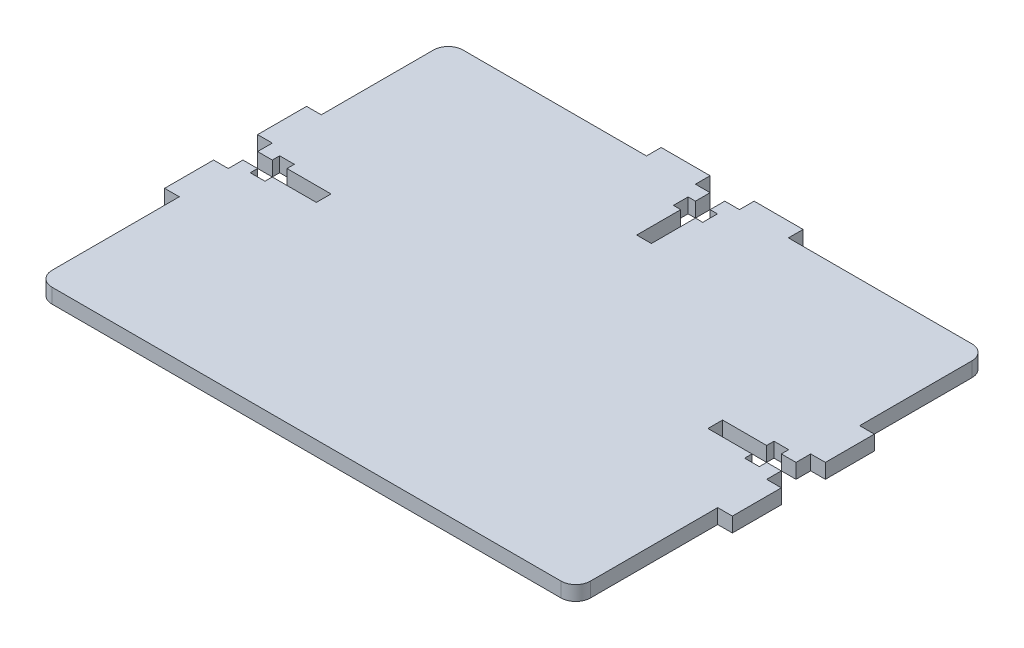
SolidWorks part; units mm, degrees
material "Acrylic (Medium-high impact)"
ref_plane "Front Plane" through (0, 0, 0) normal (0, 0, 1) x (1, 0, 0)
ref_plane "Top Plane" through (0, 0, 0) normal (0, 1, 0) x (1, 0, 0)
ref_plane "Right Plane" through (0, 0, 0) normal (1, 0, 0) x (0, 0, -1)
sketch "Sketch1" plane through (0, 0, 0) normal (0, 1, 0) x (1, 0, 0)
  line L0 (55, 83.95) -> (55, 0) construction
  line L1 (0, 0) -> (110, 0)
  line L2 (0, 83.95) -> (0, 0)
  line L3 (0, 83.95) -> (110, 83.95)
  line L4 (110, 83.95) -> (110, 0)
  line L5 (0, 41.975) -> (110, 41.975) construction
  line L6 (69.5, 83.95) -> (59.5, 83.95)
  line L7 (53.5, 83.95) -> (56.5, 83.95)
  line L8 (53.5, 83.95) -> (53.5, 68.95)
  line L9 (53.5, 68.95) -> (56.5, 68.95)
  line L10 (56.5, 83.95) -> (56.5, 68.95)
  line L11 (40.5, 83.95) -> (50.5, 83.95)
  line L12 (40.5, 83.95) -> (40.5, 86.95)
  line L13 (40.5, 86.95) -> (50.5, 86.95)
  line L14 (50.5, 83.95) -> (50.5, 86.95)
  line L15 (69.5, 83.95) -> (69.5, 86.95)
  line L16 (69.5, 86.95) -> (59.5, 86.95)
  line L17 (59.5, 83.95) -> (59.5, 86.95)
  line L19 (52, 80.95) -> (58, 80.95)
  line L20 (52, 80.95) -> (52, 77.95)
  line L21 (52, 77.95) -> (58, 77.95)
  line L22 (15, 43.5) -> (0, 43.5) construction
  line L23 (0, 45) -> (15, 45)
  line L24 (0, 45) -> (0, 42)
  line L25 (0, 42) -> (15, 42)
  line L26 (15, 45) -> (15, 42)
  line L27 (3, 46.5) -> (6, 46.5)
  line L28 (3, 46.5) -> (3, 40.5)
  line L29 (3, 40.5) -> (6, 40.5)
  line L30 (6, 46.5) -> (6, 40.5)
  line L31 (0, 29) -> (0, 39)
  line L32 (0, 58) -> (-3, 58)
  line L33 (0, 58) -> (0, 48)
  line L34 (0, 48) -> (-3, 48)
  line L35 (-3, 58) -> (-3, 48)
  line L36 (0, 39) -> (-3, 39)
  line L37 (-3, 29) -> (-3, 39)
  line L38 (0, 29) -> (-3, 29)
  line L39 (107, 46.5) -> (104, 46.5)
  line L40 (107, 46.5) -> (107, 40.5)
  line L41 (107, 40.5) -> (104, 40.5)
  line L42 (104, 46.5) -> (104, 40.5)
  line L43 (110, 45) -> (110, 42)
  line L44 (110, 42) -> (95, 42)
  line L45 (95, 45) -> (95, 42)
  line L46 (110, 45) -> (95, 45)
  line L47 (110, 58) -> (113, 58)
  line L48 (110, 58) -> (110, 48)
  line L49 (110, 48) -> (113, 48)
  line L50 (113, 58) -> (113, 48)
  line L51 (110, 29) -> (113, 29)
  line L52 (110, 29) -> (110, 39)
  line L53 (110, 39) -> (113, 39)
  line L54 (113, 29) -> (113, 39)
  line L55 (10, 0) -> (100, 0) construction
  line L56 (10, 0) -> (10, 10) construction
  line L57 (10, 10) -> (100, 10) construction
  line L58 (100, 0) -> (100, 10) construction
  line L59 (58, 80.95) -> (58, 77.95)
  point P13 (55, 68.95)
  point P26 (55, 77.95)
  point P38 (6, 43.5)
  point P67 (55, 10)
  dimension "D1" = 83.95
  dimension "D2" = 110
  dimension "D3" = 15
  dimension "D4" = 3
  dimension "D5" = 3
  dimension "D6" = 10
  dimension "D7" = 4.5
  dimension "D8" = 3
  dimension "D9" = 3
  dimension "D10" = 6
  dimension "D11" = 3
  dimension "D12" = 15
  dimension "D13" = 6
  dimension "D14" = 3
  dimension "D15" = 3
  dimension "D16" = 10
  dimension "D17" = 3
  dimension "D18" = 4.5
  dimension "D19" = 90
  dimension "D20" = 10
  dimension "D21" = 40.45
extrude "Boss-Extrude1" add sketch "Sketch1" along normal blind 3
fillet "Fillet1" radius 3 4 edges at (110, 1.5, -83.95) (110, 1.5, 0) (0, 1.5, 0) (0, 1.5, -83.95)
